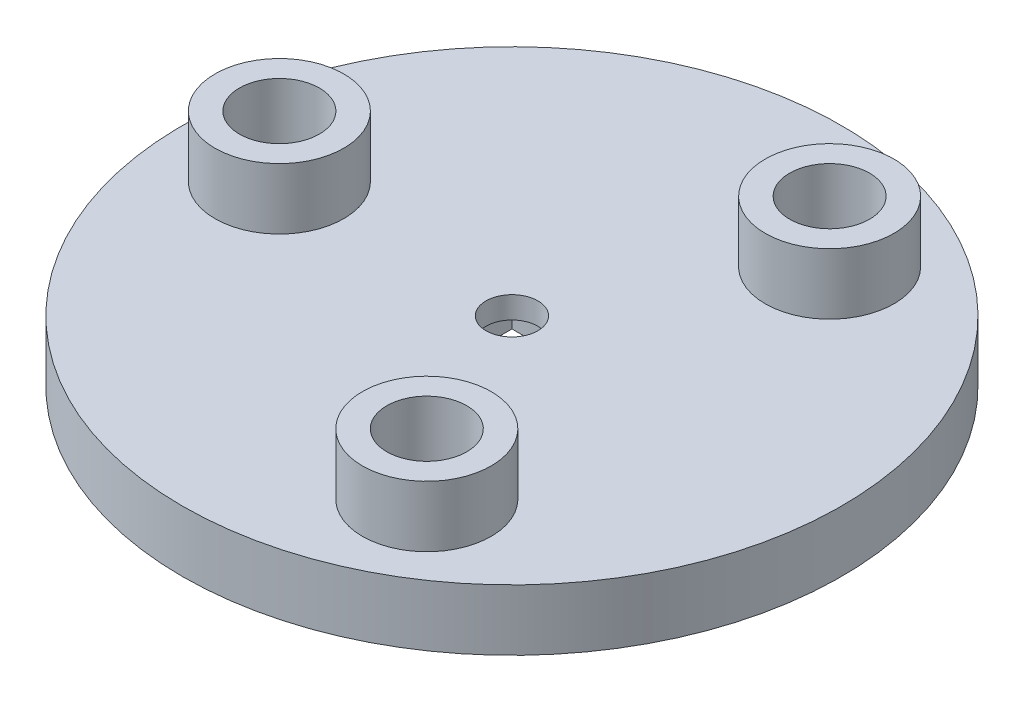
SolidWorks part; units mm, degrees
ref_plane "Front Plane" through (0, 0, 0) normal (0, 0, 1) x (1, 0, 0)
ref_plane "Top Plane" through (0, 0, 0) normal (0, 1, 0) x (1, 0, 0)
ref_plane "Right Plane" through (0, 0, 0) normal (1, 0, 0) x (0, 0, -1)
sketch "Sketch2" plane through (0, 0, 0) normal (0, 1, 0) x (1, 0, 0)
  circle A0 centre (0, 0) radius 27
  circle A1 centre (0, 0) radius 2.125
  circle A3 centre (0, 0) radius 27 construction
  point P11 (0, 0)
extrude "Boss-Extrude2" add sketch "Sketch2" along normal blind 10
sketch "Sketch3" plane through (0, 10, 0) normal (0, -1, 0) x (1, 0, 0)
  circle A3 centre (9.5263, -16.4999) radius 3.275
  circle A4 centre (9.5263, 16.4999) radius 3.275
  circle A5 centre (-19.0525, 0) radius 3.275
  circle A6 centre (9.5263, -16.4999) radius 3.175 construction
  circle A7 centre (-19.0525, 0) radius 3.175 construction
  circle A8 centre (9.5263, 16.4999) radius 3.175 construction
  dimension "D1" = 6.55
  dimension "D2" = 6.55
  dimension "D3" = 6.55
extrude "Cut-Extrude1" cut sketch "Sketch3" along normal blind 7.5
sketch "Sketch4" plane through (0, 10, 0) normal (0, 1, 0) x (1, 0, 0)
  arc A23 (-13.7775, 0) -> (-13.7775, 0) centre (-19.0525, 0) ccw
  circle A24 centre (-19.0525, 0) radius 5.275
  arc A30 (14.8013, -16.4999) -> (14.8013, -16.4999) centre (9.5263, -16.4999) ccw
  circle A31 centre (9.5263, -16.4999) radius 5.275
  circle A32 centre (0, 0) radius 27 construction
  arc A33 (14.8012, 16.4999) -> (14.8012, 16.4999) centre (9.5263, 16.4999) ccw
  circle A34 centre (9.5263, 16.4999) radius 5.275
  circle A35 centre (0, 0) radius 27
  dimension "D1" = 2
  dimension "D2" = 2
  dimension "D3" = 2
extrude "Cut-Extrude2" cut sketch "Sketch4" against normal blind 5
sketch "Sketch5" plane through (0, 0, 0) normal (0, -1, 0) x (1, 0, 0)
  line L0 (4.064, -4.065) -> (-4.064, -4.065)
  line L1 (4.064, -4.065) -> (4.064, 4.065)
  line L2 (-4.064, -4.065) -> (-4.064, 4.065)
  line L3 (4.064, 4.065) -> (-4.064, 4.065)
  line L4 (4.064, -4.065) -> (-4.064, 4.065) construction
  line L5 (-4.064, -4.065) -> (4.064, 4.065) construction
  point P1 (0, 0)
  dimension "D1" = 8.13
  dimension "D2" = 8.128
extrude "Cut-Extrude3" cut sketch "Sketch5" against normal blind 3.2
